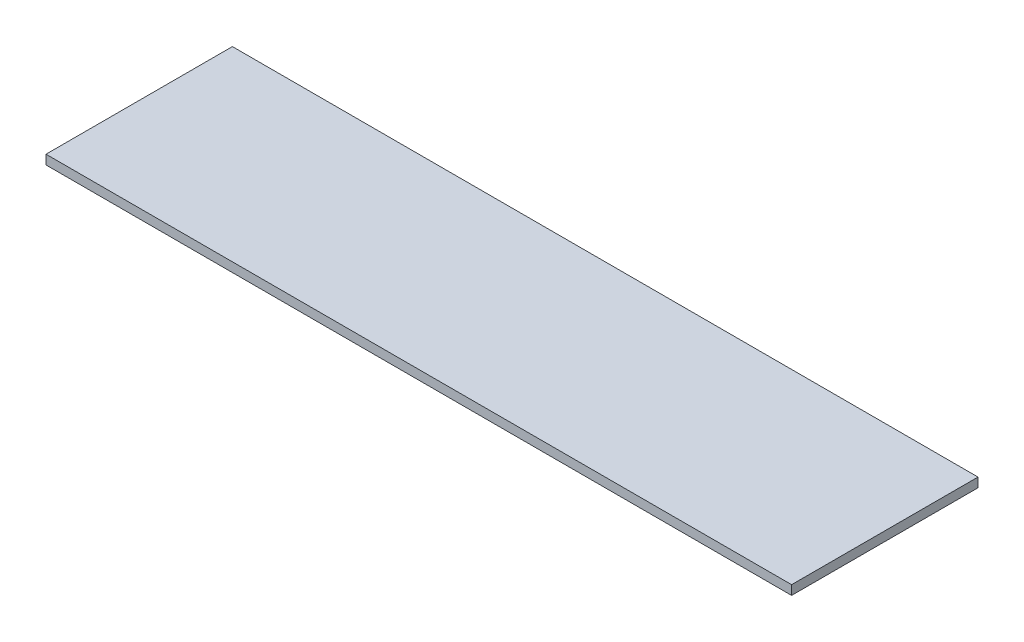
SolidWorks part; units mm, degrees
ref_plane "Front Plane" through (0, 0, 0) normal (0, 0, 1) x (1, 0, 0)
ref_plane "Top Plane" through (0, 0, 0) normal (0, 1, 0) x (1, 0, 0)
ref_plane "Right Plane" through (0, 0, 0) normal (1, 0, 0) x (0, 0, -1)
sketch "Sketch1" plane through (0, 0, 0) normal (0, 1, 0) x (1, 0, 0)
  line L1 (-200, 50) -> (200, 50)
  line L2 (-200, 50) -> (-200, -50)
  line L3 (-200, -50) -> (200, -50)
  line L4 (200, 50) -> (200, -50)
  line L5 (-200, 50) -> (200, -50) construction
  line L6 (-200, -50) -> (200, 50) construction
  point P0 (0, 0)
extrude "Boss-Extrude1" add sketch "Sketch1" along normal blind 5
